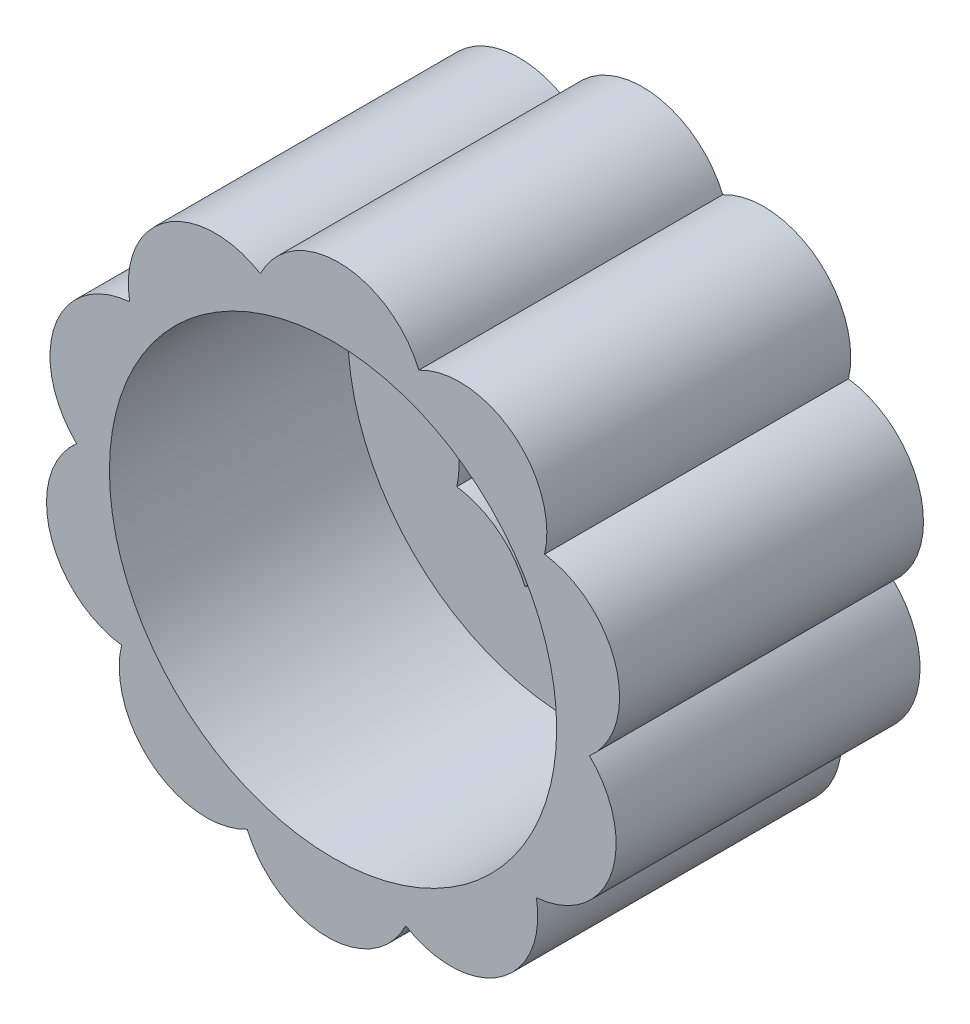
SolidWorks part; units mm, degrees
ref_plane "前视基准面" through (0, 0, 0) normal (0, 0, 1) x (1, 0, 0)
ref_plane "上视基准面" through (0, 0, 0) normal (0, 1, 0) x (1, 0, 0)
ref_plane "右视基准面" through (0, 0, 0) normal (1, 0, 0) x (0, 0, -1)
sketch "草图1" plane through (0, 0, 0) normal (0, 0, 1) x (1, 0, 0)
  arc A0 (-20.8029, 70.4289) -> (-58.2269, 44.7505) centre (-33.6943, 49.1067) ccw
  arc A1 (-11.2866, 38.2111) -> (13.3289, 37.5475) centre (1.6049, 59.5332) ccw
  arc A2 (13.3289, 37.5475) -> (32.8531, 22.542) centre (36.2911, 47.22) ccw
  arc A3 (32.8531, 22.542) -> (39.8286, -1.0737) centre (57.1154, 16.8704) ccw
  arc A4 (39.8286, -1.0737) -> (31.5909, -24.2793) centre (56.1235, -19.9231) ccw
  arc A5 (31.5909, -24.2793) -> (11.2866, -38.2111) centre (33.6943, -49.1067) ccw
  arc A6 (11.2866, -38.2111) -> (-13.3289, -37.5475) centre (-1.6049, -59.5332) ccw
  arc A7 (-13.3289, -37.5475) -> (-32.8531, -22.542) centre (-36.2911, -47.22) ccw
  arc A8 (-32.8531, -22.542) -> (-39.8286, 1.0737) centre (-57.1154, -16.8704) ccw
  arc A9 (-39.8286, 1.0737) -> (-31.5909, 24.2793) centre (-56.1235, 19.9231) ccw
  arc A10 (24.5672, 69.2058) -> (-20.8029, 70.4289) centre (1.6049, 59.5332) ccw
  arc A11 (60.5534, 41.5484) -> (24.5672, 69.2058) centre (36.2911, 47.22) ccw
  arc A12 (73.4103, -1.979) -> (60.5534, 41.5484) centre (57.1154, 16.8704) ccw
  arc A13 (58.2269, -44.7505) -> (73.4103, -1.979) centre (56.1235, -19.9231) ccw
  arc A14 (20.8029, -70.4289) -> (58.2269, -44.7505) centre (33.6943, -49.1067) ccw
  arc A15 (-24.5672, -69.2058) -> (20.8029, -70.4289) centre (-1.6049, -59.5332) ccw
  arc A16 (-60.5534, -41.5484) -> (-24.5672, -69.2058) centre (-36.2911, -47.22) ccw
  arc A17 (-73.4103, 1.979) -> (-60.5534, -41.5484) centre (-57.1154, -16.8704) ccw
  arc A18 (-31.5909, 24.2793) -> (-11.2866, 38.2111) centre (-33.6943, 49.1067) ccw
  arc A19 (-58.2269, 44.7505) -> (-73.4103, 1.979) centre (-56.1235, 19.9231) ccw
  point P23 (0, 0)
  dimension "D1" = 10
extrude "凸台-拉伸1" add sketch "草图1" along normal blind 87
ref_axis "基准轴1" through (0, 0, 0) along (0, 0, 1)
sketch "草图2" plane through (0, 0, 0) normal (0, 1, 0) x (1, 0, 0)
  line L1 (-64.0211, -18.7262) -> (-33.9122, -18.7262)
  line L2 (-64.0211, -18.7262) -> (-64.0211, -99.6505)
  line L3 (-64.0211, -99.6505) -> (-33.9122, -99.6505)
  line L4 (-33.9122, -18.7262) -> (-33.9122, -99.6505)
revolve "切除-旋转1" cut sketch "草图2" angle 360 about axis through (0, 0, 0) along (0, 0, 1)
